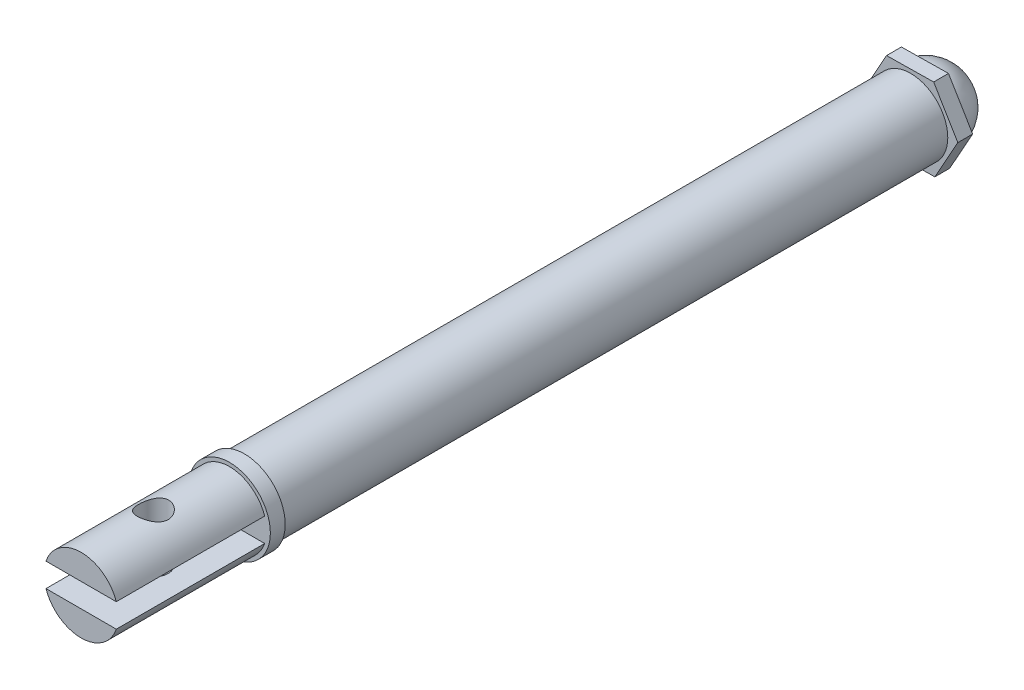
SolidWorks part; units mm, degrees
ref_plane "Front Plane" through (0, 0, 0) normal (0, 0, 1) x (1, 0, 0)
ref_plane "Top Plane" through (0, 0, 0) normal (0, 1, 0) x (1, 0, 0)
ref_plane "Right Plane" through (0, 0, 0) normal (1, 0, 0) x (0, 0, -1)
sketch "Sketch1" plane through (0, 0, 0) normal (0, 0, 1) x (1, 0, 0)
  circle A0 centre (0, 0) radius 2.5
  dimension "D1" = 5
extrude "Boss-Extrude1" add sketch "Sketch1" against normal blind 59.4
sketch "Sketch2" plane through (0, 0, 0) normal (0, 0, 1) x (1, 0, 0)
  line L0 (-2.3685, 0.8) -> (2.3685, 0.8)
  line L1 (-2.3685, -0.8) -> (2.3685, -0.8)
  circle A0 centre (0, 0) radius 2.5 construction
  arc A1 (-2.3685, 0.8) -> (-2.3685, -0.8) centre (0, 0) ccw
  arc A2 (2.3685, -0.8) -> (2.3685, 0.8) centre (0, 0) ccw
  dimension "D1" = 1.6
  dimension "D2" = 0.8
extrude "Cut-Extrude1" cut sketch "Sketch2" against normal blind 10
ref_plane "Plane1" through (0, 0, -10) normal (0, 0, 1) x (1, 0, 0)
sketch "Sketch3" plane through (0, 0, -10) normal (0, 0, 1) x (1, 0, 0)
  circle A0 centre (0, 0) radius 2.75
  dimension "D1" = 5.5
extrude "Boss-Extrude2" add sketch "Sketch3" against normal blind 1
fillet "Fillet1" radius 2.5 1 edges at (2.5, 0, -59.4)
ref_plane "Plane2" through (0, 0, -56.9) normal (0, 0, 1) x (1, 0, 0)
sketch "Sketch4" plane through (0, 0, -56.9) normal (0, 0, 1) x (1, 0, 0)
  line L1 (1.5478, 2.7727) -> (-1.6273, 2.7268)
  line L2 (-1.6273, 2.7268) -> (-3.1751, -0.0459)
  line L3 (-3.1751, -0.0459) -> (-1.5478, -2.7727)
  line L4 (-1.5478, -2.7727) -> (1.6273, -2.7268)
  line L5 (1.6273, -2.7268) -> (3.1751, 0.0459)
  line L6 (3.1751, 0.0459) -> (1.5478, 2.7727)
  circle A0 centre (0, 0) radius 2.75 construction
  dimension "D1" = 5.5
extrude "Boss-Extrude3" add sketch "Sketch4" along normal blind 1
sketch "Sketch5" plane through (0, 0, 0) normal (0, 1, 0) x (1, 0, 0)
  line L0 (-2.3685, 0) -> (2.3685, 0) construction
  line L1 (2.3685, 10) -> (2.3685, 0) construction
  circle A0 centre (-0.1315, 5) radius 1
  dimension "D1" = 2
  dimension "D3" = 2.5
  dimension "D2" = 5
extrude "Cut-Extrude2" cut sketch "Sketch5" against normal through all both and the other way through all
